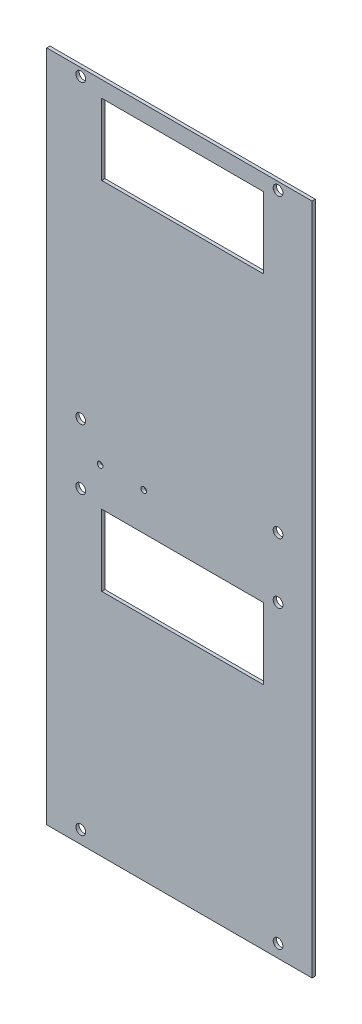
SolidWorks part; units mm, degrees
material "CFRP"
ref_plane "Front Plane" through (0, 0, 0) normal (0, 0, 1) x (1, 0, 0)
ref_plane "Top Plane" through (0, 0, 0) normal (0, 1, 0) x (1, 0, 0)
ref_plane "Right Plane" through (0, 0, 0) normal (1, 0, 0) x (0, 0, -1)
sketch "Sketch1" plane through (0, 0, 0) normal (0, 0, 1) x (1, 0, 0)
  line L1 (41, -104) -> (-41, -104)
  line L2 (41, -104) -> (41, 104)
  line L3 (41, 104) -> (-41, 104)
  line L4 (-41, -104) -> (-41, 104)
  line L5 (41, -104) -> (-41, 104) construction
  line L6 (41, 104) -> (-41, -104) construction
  point P0 (0, 0)
  dimension "D1" = 82
  dimension "D2" = 208
extrude "Boss-Extrude1" add sketch "Sketch1" along normal blind 1
hole_wizard "Ø3.0 (3) Diameter Hole1" positions "Sketch3" profile "Sketch2" hole size "Ø3.0" standard "ANSI Metric"
sketch "Sketch3" plane through (0, 0, 1) normal (0, 0, 1) x (1, 0, 0)
  line L6 (-41, -104) -> (41, -104) construction
  line L7 (0, -104) -> (0, -71.8918) construction
  line L8 (-41, -104) -> (41, -104) construction
  line L9 (0, 0) -> (0, 113.4273) construction
  line L11 (41, 104) -> (-41, 104) construction
  point P0 (-30.5, 10)
  point P2 (30.5, 10)
  point P15 (30.5, -100)
  point P17 (-30.5, -100)
  point P36 (-30.5, 101.6)
  point P40 (30.5, 101.6)
  point P48 (30.5, -8.7)
  point P53 (-30.5, -8.7)
  dimension "D11" = 30.5
  dimension "D1" = 30.5
  dimension "D2" = 4
  dimension "D3" = 30.5
  dimension "D4" = 4
  dimension "D5" = 94
  dimension "D6" = 94
  dimension "D7" = 30.5
  dimension "D8" = 30.5
  dimension "D9" = 30.5
sketch "Sketch2" plane through (-30.5, 10, 1) normal (1, 0, 0) x (0, -1, 0)
  line L0 (0, 0) -> (0, 1)
  line L1 (0, 1) -> (1.5, 1)
  line L2 (1.5, 1) -> (1.5, 0)
  line L5 (1.5, 0) -> (0, 0)
  line L10 (0, 1) -> (-1.5, 1) construction
  line L11 (0, -6.35) -> (0, 107.95) construction
  dimension "Hole Dia." = 3
  dimension "Hole Depth" = 1
  dimension "Drill Angle" = 180
sketch "Sketch7" plane through (0, 0, 0) normal (0, 0, -1) x (-1, 0, 0)
  line L0 (41, -104) -> (-41, -104) construction
  line L5 (-26, -33) -> (24, -33)
  line L6 (-26, -33) -> (-26, -11)
  line L7 (-26, -11) -> (24, -11)
  line L8 (24, -33) -> (24, -11)
  line L9 (-41, -104) -> (-41, 104) construction
  line L18 (-41, 104) -> (41, 104) construction
  line L19 (-26, 77) -> (24, 77)
  line L20 (-26, 77) -> (-26, 99)
  line L21 (-26, 99) -> (24, 99)
  line L22 (24, 77) -> (24, 99)
  dimension "D3" = 22
  dimension "D4" = 71
  dimension "D5" = 50
  dimension "D7" = 15
  dimension "D9" = 15
  dimension "D13" = 50
  dimension "D14" = 22
  dimension "D15" = 5
extrude "Cut-Extrude1" cut sketch "Sketch7" against normal blind 10
hole_wizard "Ø1.75 (1.75) Diameter Hole1" positions "Sketch9" profile "Sketch8" hole size "Ø1.75" standard "ANSI Metric" end condition through all
sketch "Sketch9" plane through (0, 0, 0) normal (0, 0, -1) x (-1, 0, 0)
  point P0 (24.5, 0.65)
  point P3 (11, 0.65)
sketch "Sketch8" plane through (-24.5, 0.65, 0) normal (1, 0, 0) x (0, 1, 0)
  line L0 (0, 0) -> (0, 1)
  line L1 (0, 1) -> (0.875, 1)
  line L2 (0.875, 1) -> (0.875, 0)
  line L5 (0.875, 0) -> (0, 0)
  line L11 (0, -6.35) -> (0, 107.95) construction
  dimension "Thru Hole Dia." = 1.75
  dimension "Thru Hole Depth" = 1
